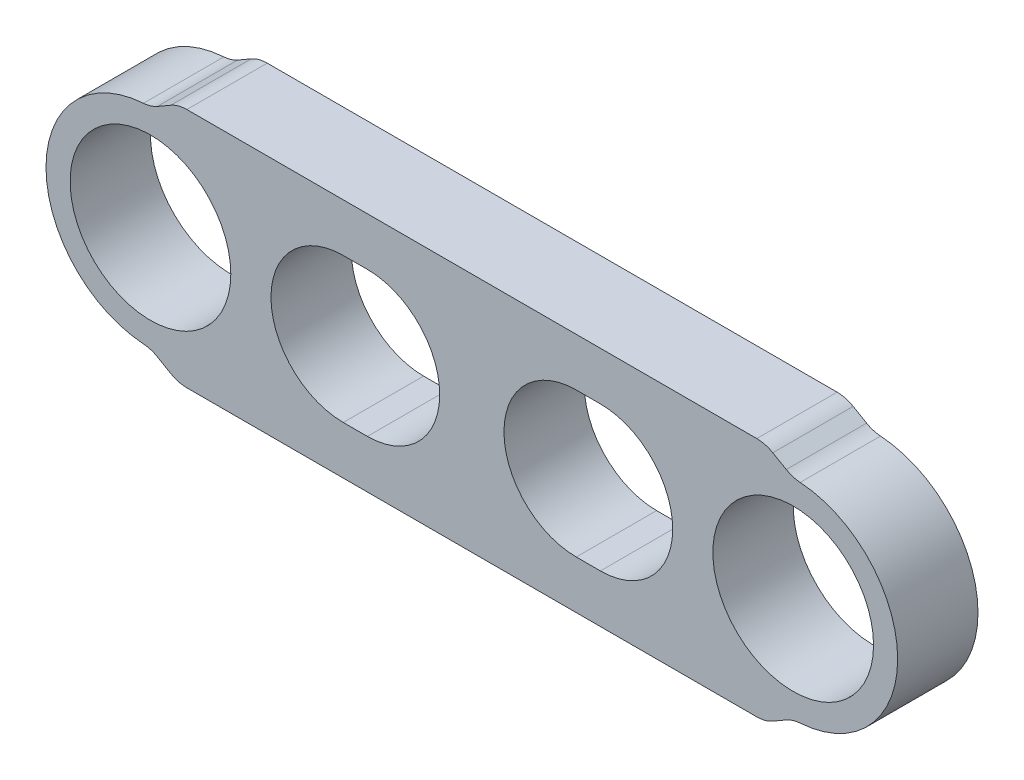
SolidWorks part; units mm, degrees
ref_plane "前视基准面" through (0, 0, 0) normal (0, 0, 1) x (1, 0, 0)
ref_plane "上视基准面" through (0, 0, 0) normal (0, 1, 0) x (1, 0, 0)
ref_plane "右视基准面" through (0, 0, 0) normal (1, 0, 0) x (0, 0, -1)
sketch "草图1" plane through (0, 0, 0) normal (0, 0, 1) x (1, 0, 0)
  line L0 (0, 0) -> (40, 0) construction
  line L1 (0, 0) -> (40, 0) construction
  line L2 (0, 7.5) -> (40, 7.5)
  line L3 (0, -7.5) -> (40, -7.5)
  circle A0 centre (0, 0) radius 3.5
  circle A1 centre (40, 0) radius 3.5
  arc A2 (0, 7.5) -> (0, -7.5) centre (0, 0) ccw
  arc A3 (40, -7.5) -> (40, 7.5) centre (40, 0) ccw
  point P5 (20, 0)
  dimension "D2" = 7
  dimension "D3" = 7.5
  dimension "D1" = 40
extrude "凸台-拉伸1" add sketch "草图1" along normal blind 5
sketch "草图3" plane through (0, 0, 5) normal (0, 0, 1) x (1, 0, 0)
  line L0 (20, 7.5) -> (20, -15.9011) construction
  line L1 (40, 7.5) -> (0, 7.5) construction
  line L2 (0, 6.5) -> (1.7321, 7.5)
  line L3 (40, 6.5) -> (38.2679, 7.5)
  line L4 (0, 0) -> (40, 0) construction
  line L5 (40, -6.5) -> (38.2679, -7.5)
  line L6 (0, -6.5) -> (1.7321, -7.5)
  circle A0 centre (0, 0) radius 6.5
  circle A1 centre (40, 0) radius 6.5
  arc M7 (0, 7.5) -> (0, -7.5) centre (0, 0) ccw
  line M8 (0, -7.5) -> (40, -7.5)
  arc M9 (40, -7.5) -> (40, 7.5) centre (40, 0) ccw
  line M10 (40, 7.5) -> (0, 7.5)
  dimension "D1" = 13
  dimension "D2" = 60
extrude "切除-拉伸2" cut sketch "草图3" against normal through all contours A0 L2 L6 M10 M7 M8 | L3 A1 L5 M8 M9 M10
sketch "草图4" plane through (0, 0, 5) normal (0, 0, 1) x (1, 0, 0)
  line L0 (20, 7.5) -> (20, -7.5) construction
  line L1 (38.2679, 7.5) -> (1.7321, 7.5) construction
  line L2 (1.7321, -7.5) -> (38.2679, -7.5) construction
  line L3 (0, 0) -> (40, 0) construction
  line L4 (12, 0) -> (13.5, 0) construction
  line L5 (12, 4.5) -> (13.5, 4.5)
  line L6 (12, -4.5) -> (13.5, -4.5)
  line L7 (28, 0) -> (26.5, 0) construction
  line L8 (28, 4.5) -> (26.5, 4.5)
  line L9 (28, -4.5) -> (26.5, -4.5)
  line L11 (38.2679, 7.5) -> (1.7321, 7.5) construction
  arc A0 (12, 4.5) -> (12, -4.5) centre (12, 0) ccw
  arc A1 (13.5, -4.5) -> (13.5, 4.5) centre (13.5, 0) ccw
  arc A2 (28, 4.5) -> (28, -4.5) centre (28, 0) cw
  arc A3 (26.5, -4.5) -> (26.5, 4.5) centre (26.5, 0) cw
  point P12 (12.75, 0)
  point P19 (27.25, 0)
  dimension "D3" = 3
  dimension "D1" = 12
  dimension "D2" = 6.5
sketch "草图6" plane through (0, 0, 5) normal (0, 0, 1) x (1, 0, 0)
  circle A0 centre (0, 0) radius 5
  circle A1 centre (40, 0) radius 5
  dimension "D1" = 10
  dimension "D2" = 10
extrude "切除-拉伸3" cut sketch "草图6" against normal blind 6
extrude "切除-拉伸4" cut sketch "草图4" against normal blind 10
fillet "圆角1" radius 2 8 edges at (1.7321, -7.5, 2.5) (38.2679, -7.5, 2.5) (40, -6.5, 2.5) (40, 6.5, 2.5) (38.2679, 7.5, 2.5) (0, 6.5, 2.5) (0, -6.5, 2.5) (1.7321, 7.5, 2.5)
